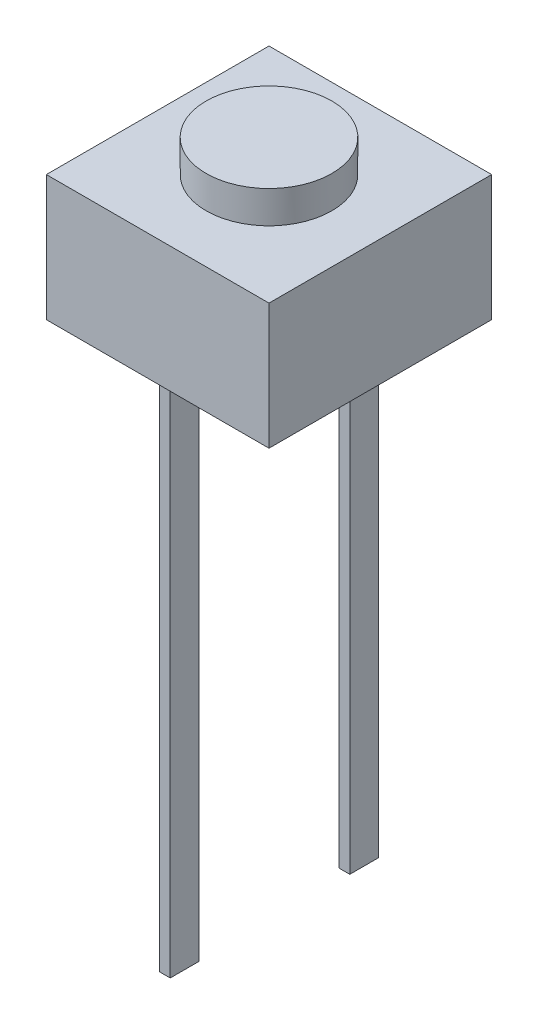
SolidWorks part; units mm, degrees
ref_plane "Спереди" through (0, 0, 0) normal (0, 0, 1) x (1, 0, 0)
ref_plane "Сверху" through (0, 0, 0) normal (0, 1, 0) x (1, 0, 0)
ref_plane "Справа" through (0, 0, 0) normal (1, 0, 0) x (0, 0, -1)
other "Configuration Table"
sketch "Эскиз1" plane through (0, 0, 0) normal (0, 1, 0) x (1, 0, 0)
  line L1 (-3.1, -3.1) -> (3.1, -3.1)
  line L2 (-3.1, -3.1) -> (-3.1, 3.1)
  line L3 (-3.1, 3.1) -> (3.1, 3.1)
  line L4 (3.1, -3.1) -> (3.1, 3.1)
  line L5 (-3.1, -3.1) -> (3.1, 3.1) construction
  line L6 (-3.1, 3.1) -> (3.1, -3.1) construction
  point P0 (0, 0)
  dimension "D1" = 6.2
extrude "Бобышка-Вытянуть1" add sketch "Эскиз1" along normal blind 3.5
sketch "Эскиз2" plane through (0, 3.5, 0) normal (0, 1, 0) x (1, 0, 0)
  circle A0 centre (0, 0) radius 1.75
  dimension "D1" = 3.5
extrude "Бобышка-Вытянуть2" add sketch "Эскиз2" along normal offset from surface (0.9 mm away) 4.4 up to face at (0, 0, 0)
sketch "Эскиз3" plane through (0, 0, 0) normal (0, -1, 0) x (1, 0, 0)
  line L0 (-0.15, 2.1) -> (-0.15, 2.9)
  line L1 (-0.15, 2.1) -> (0.15, 2.1)
  line L2 (-0.15, 2.9) -> (0.15, 2.9)
  line L3 (0.15, 2.1) -> (0.15, 2.9)
  line L4 (-0.15, 2.1) -> (0.15, 2.9) construction
  line L5 (-0.15, 2.9) -> (0.15, 2.1) construction
  line L6 (-0.15, -2.1) -> (-0.15, -2.9)
  line L7 (-0.15, -2.1) -> (0.15, -2.1)
  line L8 (-0.15, -2.9) -> (0.15, -2.9)
  line L9 (0.15, -2.1) -> (0.15, -2.9)
  line L10 (-0.15, -2.1) -> (0.15, -2.9) construction
  line L11 (-0.15, -2.9) -> (0.15, -2.1) construction
  point P0 (0, 0)
  point P1 (0, 2.5)
  point P2 (0, -2.5)
  dimension "D1" = 0.3
  dimension "D2" = 5
  dimension "D3" = 2.5
  dimension "D4" = 0.8
extrude "Бобышка-Вытянуть3" add sketch "Эскиз3" along normal blind 14.35
